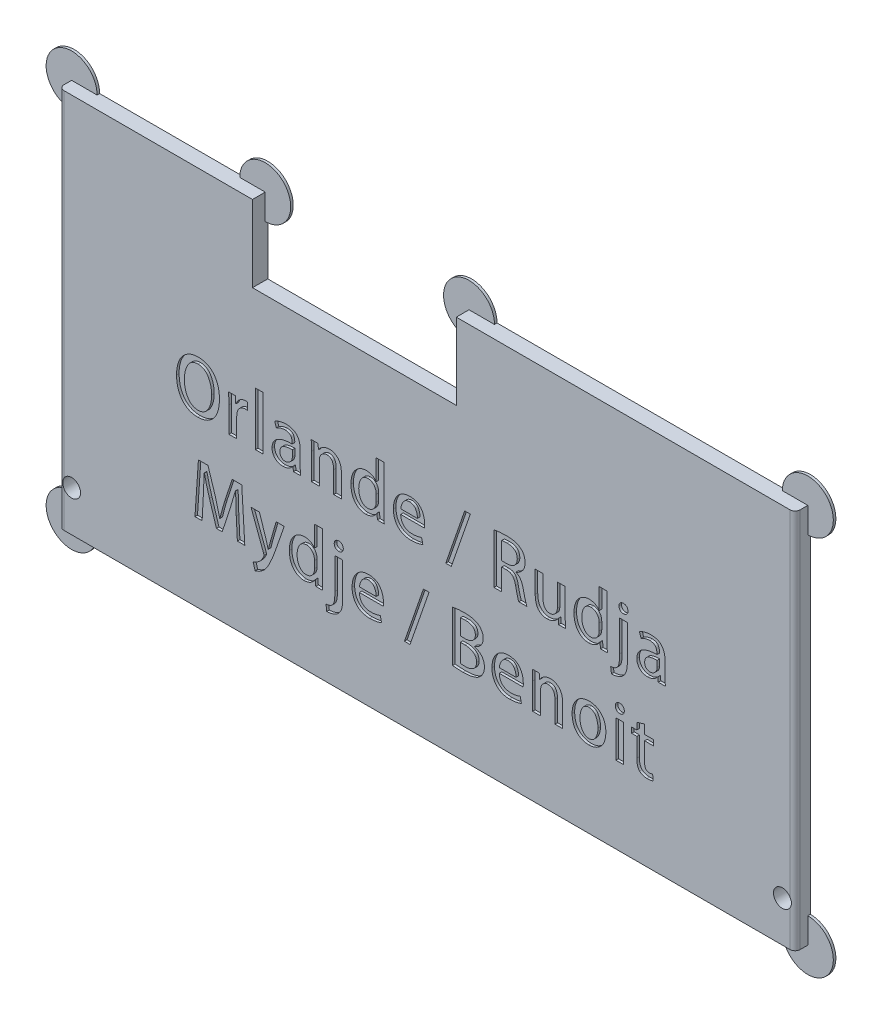
SolidWorks part; units mm, degrees
material "ABS"
ref_plane "Front Plane" through (0, 0, 0) normal (0, 0, 1) x (1, 0, 0)
ref_plane "Top Plane" through (0, 0, 0) normal (0, 1, 0) x (1, 0, 0)
ref_plane "Right Plane" through (0, 0, 0) normal (1, 0, 0) x (0, 0, -1)
sketch "Sketch1" plane through (0, 0, 0) normal (0, 0, 1) x (1, 0, 0)
  line L1 (-72.25, -74.75) -> (72.25, -74.75)
  line L2 (-72.25, -74.75) -> (-72.25, 74.75)
  line L3 (-72.25, 74.75) -> (72.25, 74.75)
  line L4 (72.25, -74.75) -> (72.25, 74.75)
  line L5 (-72.25, -74.75) -> (72.25, 74.75) construction
  line L6 (-72.25, 74.75) -> (72.25, -74.75) construction
  point P0 (0, 0)
  dimension "D1" = 144.5
  dimension "D2" = 149.5
extrude "Boss-Extrude1" add sketch "Sketch1" along normal blind 3
sketch "Sketch2" plane through (0, 0, 3) normal (0, 0, 1) x (1, 0, 0)
  line L0 (72.25, 0) -> (-72.25, 0) construction
  line L1 (72.25, -74.75) -> (72.25, 74.75) construction
  line L2 (-72.25, 74.75) -> (-72.25, -74.75) construction
  line L4 (-34.25, 15) -> (5.75, 15)
  line L5 (-34.25, 15) -> (-34.25, -15)
  line L6 (-34.25, -15) -> (5.75, -15)
  line L7 (5.75, 15) -> (5.75, -15)
  line L8 (-34.25, 15) -> (5.75, -15) construction
  line L9 (-34.25, -15) -> (5.75, 15) construction
  point P6 (-14.25, 0)
  dimension "D1" = 30
  dimension "D2" = 40
  dimension "D3" = 58
extrude "Cut-Extrude1" cut sketch "Sketch2" against normal up to next
sketch "Esquisse1" plane through (0, 0, 3) normal (0, 0, 1) x (1, 0, 0)
  line L0 (72.25, -74.75) -> (72.25, 74.75) construction
  line L1 (-72.25, 74.75) -> (72.25, 74.75)
  line L2 (-72.25, 74.75) -> (-72.25, 0)
  line L3 (-72.25, 0) -> (72.25, 0)
  line L4 (72.25, 74.75) -> (72.25, 0)
extrude "Enlèv. mat.-Extru.1" cut sketch "Esquisse1" against normal blind 10
fillet "Congé1" radius 1 2 edges at (-72.25, -37.375, 3) (72.25, -37.375, 3)
sketch "Esquisse2" plane through (0, 0, 0) normal (0, 0, -1) x (-1, 0, 0)
  line L0 (69.75, 0) -> (69.75, -74.75) construction
  line L1 (34.25, 0) -> (72.25, 0) construction
  line L2 (72.25, -74.75) -> (-72.25, -74.75) construction
  line L3 (72.25, 0) -> (72.25, -74.75) construction
  line L4 (0, 0) -> (0, -74.75) construction
  line L5 (-69.75, 0) -> (-69.75, -74.75) construction
  circle A0 centre (69.75, -66.75) radius 1.75
  circle A1 centre (-69.75, -66.75) radius 1.75
  dimension "D2" = 3.5
  dimension "D1" = 2.5
  dimension "D3" = 8
extrude "Enlèv. mat.-Extru.2" cut sketch "Esquisse2" against normal blind 10
sketch "Esquisse3" plane through (0, 0, 0) normal (0, 0, -1) x (-1, 0, 0)
  line L0 (34.25, 0) -> (72.25, 0) construction
  line L1 (34.25, 0) -> (34.25, -15) construction
  circle A0 centre (72.25, 0) radius 5
  circle A1 centre (72.25, -74.75) radius 5
  circle A2 centre (-72.25, -74.75) radius 5
  circle A3 centre (-72.25, 0) radius 5
  circle A4 centre (-5.75, 0) radius 5
  circle A5 centre (34.25, 0) radius 5
  dimension "D1" = 10
extrude "Boss.-Extru.1" add sketch "Esquisse3" against normal blind 0.5
sketch "Esquisse4" plane through (0, 0, 3) normal (0, 0, 1) x (1, 0, 0)
  text T0 "<b>Orlande / Rudja </b>\r\n<b> Mydje / Benoit</b>" font "@Adobe Heiti Std R" height 10
extrude "Enlèv. mat.-Extru.5" cut sketch "Esquisse4" against normal blind 0.5
